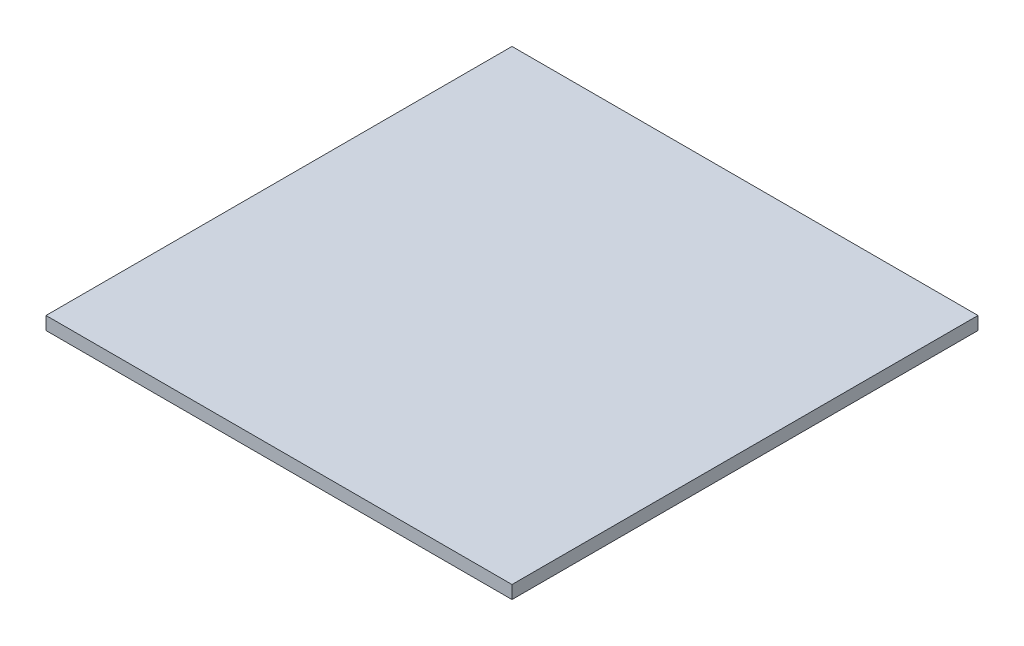
SolidWorks part; units mm, degrees
ref_plane "Front Plane" through (0, 0, 0) normal (0, 0, 1) x (1, 0, 0)
ref_plane "Top Plane" through (0, 0, 0) normal (0, 1, 0) x (1, 0, 0)
ref_plane "Right Plane" through (0, 0, 0) normal (1, 0, 0) x (0, 0, -1)
sketch "Sketch1" plane through (0, 0, 0) normal (0, 1, 0) x (1, 0, 0)
  line L1 (-107, 0) -> (-107, 107)
  line L2 (-107, 107) -> (107, 107)
  line L3 (107, 107) -> (107, -107)
  line L4 (107, -107) -> (-107, -107)
  line L5 (-107, -107) -> (-107, 0)
extrude "Boss-Extrude1" add sketch "Sketch1" along normal blind 6
